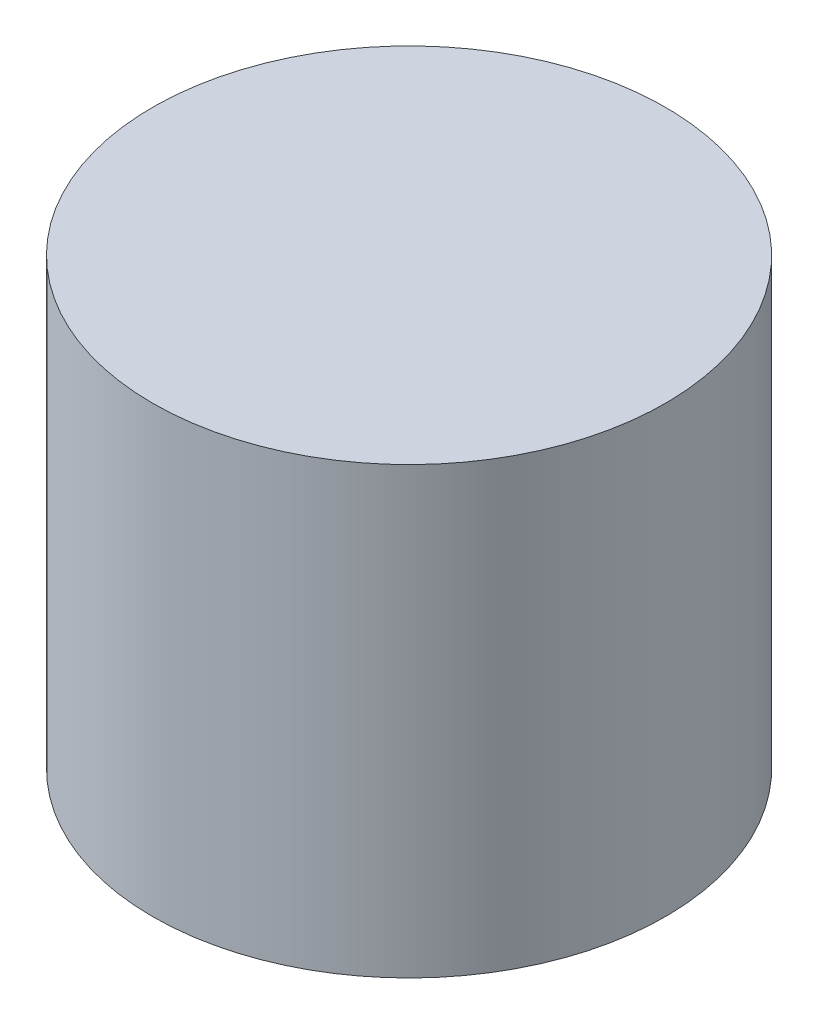
SolidWorks part; units mm, degrees
ref_plane "Front Plane" through (0, 0, 0) normal (0, 0, 1) x (1, 0, 0)
ref_plane "Top Plane" through (0, 0, 0) normal (0, 1, 0) x (1, 0, 0)
ref_plane "Right Plane" through (0, 0, 0) normal (1, 0, 0) x (0, 0, -1)
sketch "Sketch1" plane through (0, 0, 0) normal (0, 1, 0) x (1, 0, 0)
  circle A0 centre (0, 0) radius 6.095
  dimension "D1" = 12.19
extrude "Boss-Extrude1" add sketch "Sketch1" along normal blind 10.57
